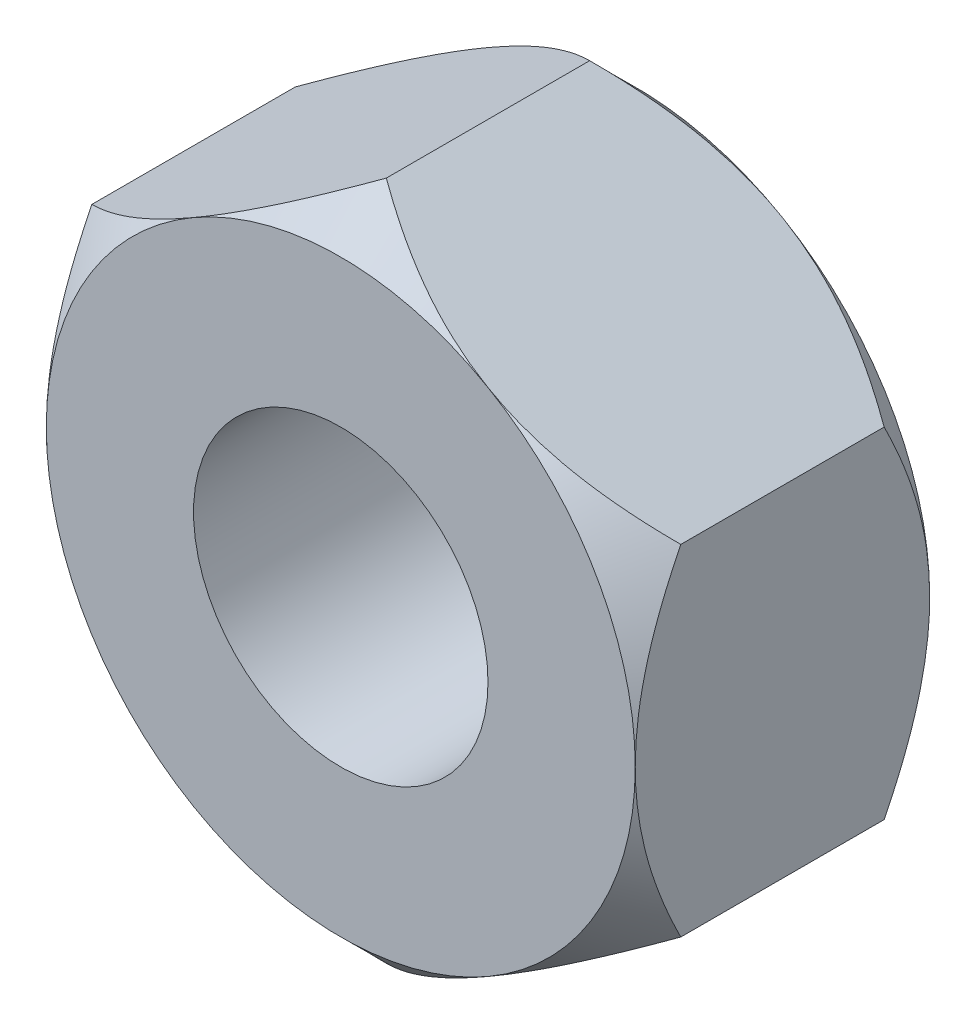
SolidWorks part; units mm, degrees
ref_plane "Front Plane" through (0, 0, 0) normal (0, 0, 1) x (1, 0, 0)
ref_plane "Top Plane" through (0, 0, 0) normal (0, 1, 0) x (1, 0, 0)
ref_plane "Right Plane" through (0, 0, 0) normal (1, 0, 0) x (0, 0, -1)
sketch "Sketch1" plane through (0, 0, 0) normal (0, 0, 1) x (1, 0, 0)
  line L1 (0, 11.547) -> (-10, 5.7735)
  line L2 (-10, 5.7735) -> (-10, -5.7735)
  line L3 (-10, -5.7735) -> (0, -11.547)
  line L4 (0, -11.547) -> (10, -5.7735)
  line L5 (10, -5.7735) -> (10, 5.7735)
  line L6 (10, 5.7735) -> (0, 11.547)
  circle A0 centre (0, 0) radius 10 construction
  dimension "D1" = 20
extrude "Extrude1" add sketch "Sketch1" along normal mid plane 10
sketch "Sketch2" plane through (0, 0, 5) normal (0, 0, 1) x (1, 0, 0)
  circle A0 centre (0, 0) radius 5
  dimension "D1" = 10
extrude "Extrude2" cut sketch "Sketch2" against normal blind 10
sketch "Sketch3" plane through (0, 0, 5) normal (0, 0, 1) x (1, 0, 0)
  circle A0 centre (0, 0) radius 10
extrude "Extrude4" cut sketch "Sketch3" against normal blind 10 draft 45 flip side to cut
sketch "Sketch4" plane through (0, 0, -5) normal (0, 0, -1) x (-1, 0, 0)
  circle A0 centre (0, 0) radius 10
extrude "Extrude5" cut sketch "Sketch4" against normal blind 10 draft 45 flip side to cut
